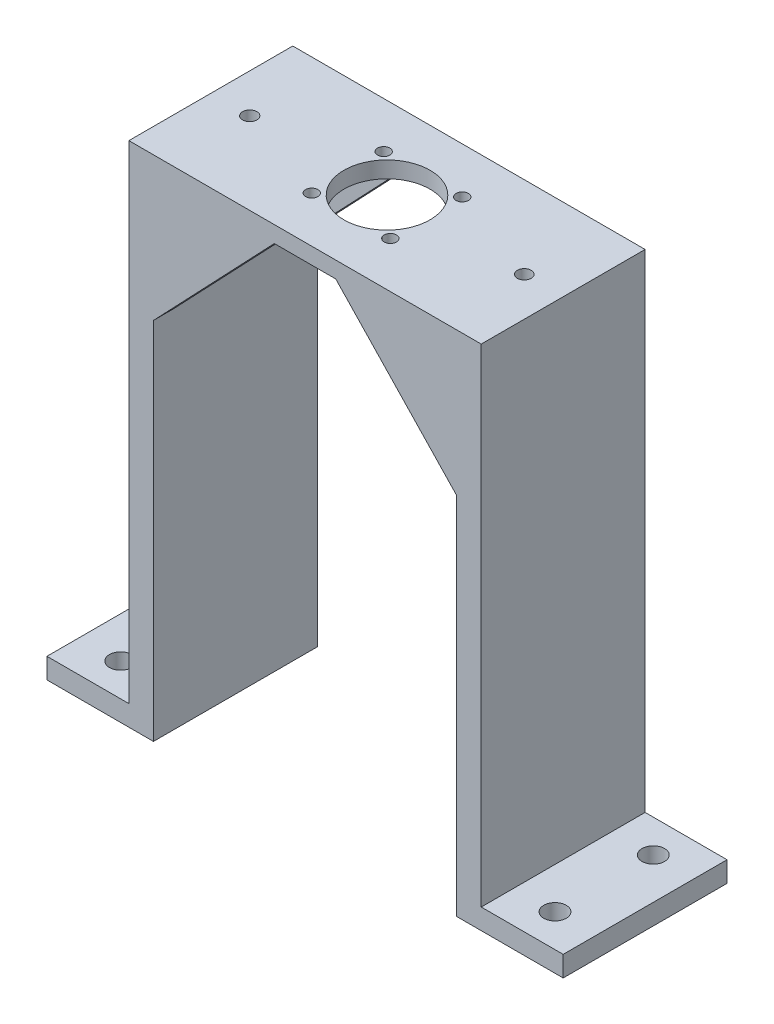
SolidWorks part; units mm, degrees
ref_plane "Plan de face" through (0, 0, 0) normal (0, 0, 1) x (1, 0, 0)
ref_plane "Plan de dessus" through (0, 0, 0) normal (0, 1, 0) x (1, 0, 0)
ref_plane "Plan de droite" through (0, 0, 0) normal (1, 0, 0) x (0, 0, -1)
sketch "Esquisse1" plane through (0, 0, 0) normal (0, 1, 0) x (1, 0, 0)
  line L1 (0, 0) -> (86, 0)
  line L2 (0, 0) -> (0, 40)
  line L3 (0, 40) -> (86, 40)
  line L4 (86, 0) -> (86, 40)
  dimension "D1" = 40
  dimension "D2" = 86
extrude "Boss.-Extru.1" add sketch "Esquisse1" along normal blind 4
sketch "Esquisse2" plane through (0, 4, 0) normal (0, 1, 0) x (1, 0, 0)
  line L0 (0, 0) -> (86, 40) construction
  line L1 (86, 40) -> (0, 40) construction
  line L2 (0, 40) -> (86, 0) construction
  line L3 (0, 0) -> (86, 0) construction
  line L4 (86, 0) -> (86, 40) construction
  circle A0 centre (43, 20) radius 10.5
  point P8 (43, 20)
  dimension "D1" = 21
  dimension "D2" = 0
extrude "Enlèv. mat.-Extru.1" cut sketch "Esquisse2" against normal through all
sketch "Esquisse3" plane through (0, 0, 0) normal (0, -1, 0) x (-1, 0, 0)
  line L0 (0, 0) -> (-86, 0) construction
  line L1 (0, 40) -> (-6, 40)
  line L2 (0, 40) -> (0, 0)
  line L3 (0, 0) -> (-6, 0)
  line L4 (-6, 40) -> (-6, 0)
  line L5 (-86, 40) -> (0, 40) construction
  line L6 (-86, 0) -> (-80, 0)
  line L7 (-86, 0) -> (-86, 40)
  line L8 (-86, 40) -> (-80, 40)
  line L9 (-80, 0) -> (-80, 40)
  dimension "D1" = 6
  dimension "D2" = 6
extrude "Boss.-Extru.2" add sketch "Esquisse3" along normal blind 120
sketch "Esquisse4" plane through (0, 0, 0) normal (-1, 0, 0) x (0, 0, 1)
  line L0 (0, 4) -> (0, -120) construction
  line L1 (-40, -120) -> (0, -120)
  line L2 (-40, -120) -> (-40, -115)
  line L3 (-40, -115) -> (0, -115)
  line L4 (0, -120) -> (0, -115)
  dimension "D1" = 5
extrude "Boss.-Extru.3" add sketch "Esquisse4" along normal blind 20
sketch "Esquisse5" plane through (86, 0, 0) normal (1, 0, 0) x (0, 0, -1)
  line L0 (40, 4) -> (40, -120) construction
  line L1 (0, -120) -> (40, -120)
  line L2 (0, -120) -> (0, -115)
  line L3 (0, -115) -> (40, -115)
  line L4 (40, -120) -> (40, -115)
  dimension "D1" = 5
extrude "Boss.-Extru.4" add sketch "Esquisse5" along normal blind 20
sketch "Esquisse6" plane through (0, -115, 0) normal (0, 1, 0) x (1, 0, 0)
  line L0 (-20, 40) -> (0, 0) construction
  line L1 (0, 0) -> (0, 40) construction
  line L2 (0, 40) -> (-20, 0) construction
  line L3 (-20, 0) -> (-20, 40) construction
  line L4 (-20, 0) -> (0, 0) construction
sketch "Esquisse7" plane through (0, -115, 0) normal (0, 1, 0) x (1, 0, 0)
  line L0 (106, 40) -> (86, 0) construction
  line L1 (86, 0) -> (106, 0) construction
  line L2 (106, 0) -> (86, 40) construction
sketch "Esquisse8" plane through (0, -115, 0) normal (0, 1, 0) x (1, 0, 0)
  line L0 (-20, 40) -> (0, 0) construction
  line L1 (0, 0) -> (-20, 0) construction
  line L2 (-20, 0) -> (0, 40) construction
  line L3 (-10, 20) -> (-10, 0) construction
  line L4 (-10, 0) -> (-10, 40) construction
  line L5 (-20, 40) -> (0, 40) construction
sketch "Esquisse9" plane through (0, -115, 0) normal (0, 1, 0) x (1, 0, 0)
  line L0 (106, 40) -> (86, 0) construction
  line L1 (86, 0) -> (106, 0) construction
  line L2 (106, 0) -> (86, 40) construction
  line L3 (86, 40) -> (86, 0) construction
  line L4 (106, 40) -> (86, 40) construction
  line L5 (96, 20) -> (96, 0) construction
  line L6 (96, 0) -> (96, 40) construction
hole_wizard "Dégagement M51" positions "Esquisse18" profile "Esquisse19" hole size "M5" standard "ISO" end condition up to next
sketch "Esquisse18" plane through (0, -115, 0) normal (0, 1, 0) x (1, 0, 0)
  line L0 (-10, 0) -> (-10, 40) construction
  line L1 (-10, 20) -> (-10, 0) construction
  line L2 (96, 0) -> (96, 40) construction
  line L3 (96, 20) -> (96, 0) construction
  point P0 (-10, 32)
  point P4 (-10, 8)
  point P8 (96, 32)
  point P12 (96, 8)
  dimension "D1" = 12
  dimension "D2" = 12
  dimension "D3" = 12
  dimension "D4" = 12
sketch "Esquisse19" plane through (-10, -115, -32) normal (1, 0, 0) x (0, 0, 1)
  line L0 (0, 0) -> (0, 5)
  line L1 (0, 5) -> (2.75, 5)
  line L2 (2.75, 5) -> (2.75, 0)
  line L5 (2.75, 0) -> (0, 0)
  line L11 (0, -6.35) -> (0, 107.95) construction
  dimension "Diamètre du perçage jusqu'au prochain" = 5.5
  dimension "Profondeur du perçage jusqu'au prochain" = 5
sketch "Esquisse32" plane through (6, 0, 0) normal (1, 0, 0) x (0, 0, -1)
  line L0 (0, -120) -> (0, 0) construction
  line L1 (40, 0) -> (0, 0)
  line L2 (40, 0) -> (40, -31)
  line L3 (40, -31) -> (0, -31)
  line L4 (0, 0) -> (0, -31)
  dimension "D1" = 31
extrude "Boss.-Extru.5" add sketch "Esquisse32" along normal blind 29.5
sketch "Esquisse33" plane through (80, 0, 0) normal (-1, 0, 0) x (0, 0, 1)
  line L0 (0, -120) -> (0, 0) construction
  line L1 (-40, 0) -> (0, 0)
  line L2 (-40, 0) -> (-40, -31)
  line L3 (-40, -31) -> (0, -31)
  line L4 (0, 0) -> (0, -31)
  dimension "D1" = 31
extrude "Boss.-Extru.6" add sketch "Esquisse33" along normal blind 29.5
sketch "Esquisse34" plane through (0, 0, 0) normal (0, 0, 1) x (1, 0, 0)
  line L0 (6, -31) -> (35.5, 0)
  line L1 (35.5, 0) -> (35.5, -31)
  line L2 (35.5, -31) -> (6, -31)
  line L3 (50.5, 0) -> (80, -31)
  line L4 (80, -31) -> (50.5, -31)
  line L5 (50.5, -31) -> (50.5, 0)
sketch "Esquisse38" plane through (0, 4, 0) normal (0, 1, 0) x (1, 0, 0)
  line L1 (52.5898, 11.2231) -> (33.4102, 11.2231)
  line L2 (52.5898, 11.2231) -> (52.5898, 28.7769)
  line L3 (52.5898, 28.7769) -> (33.4102, 28.7769)
  line L4 (33.4102, 11.2231) -> (33.4102, 28.7769)
  line L5 (52.5898, 11.2231) -> (33.4102, 28.7769) construction
  line L6 (52.5898, 28.7769) -> (33.4102, 11.2231) construction
  point P0 (43, 20)
  dimension "D1" = 26
sketch "Esquisse39" plane through (0, 4, 0) normal (0, 1, 0) x (1, 0, 0)
  circle A0 centre (33.4102, 28.7769) radius 1.5
  circle A1 centre (33.4102, 11.2231) radius 1.5
  circle A2 centre (52.5898, 11.2231) radius 1.5
  circle A3 centre (52.5898, 28.7769) radius 1.5
  dimension "D1" = 3
  dimension "D2" = 3
  dimension "D3" = 3
  dimension "D4" = 3
extrude "Enlèv. mat.-Extru.4" cut sketch "Esquisse39" against normal through all
sketch "Esquisse42" plane through (0, 0, 0) normal (0, 0, 1) x (1, 0, 0)
  line L0 (50.5, 0) -> (80, -31)
  line L1 (80, -31) -> (50.5, -31)
  line L2 (50.5, -31) -> (50.5, 0)
sketch "Esquisse43" plane through (35.5, 0, 0) normal (1, 0, 0) x (0, 0, -1)
  line L0 (27.3485, 0) -> (12.6515, 0) construction
  line L1 (5, 0) -> (35, 0)
  line L2 (5, 0) -> (5, -31)
  line L3 (5, -31) -> (35, -31)
  line L4 (35, 0) -> (35, -31)
  line L5 (0, -31) -> (40, -31) construction
  line L6 (0, 0) -> (0, -31) construction
  line L7 (40, -31) -> (40, 0) construction
  dimension "D1" = 5
  dimension "D2" = 5
sketch "Esquisse44" plane through (50.5, 0, 0) normal (-1, 0, 0) x (0, 0, 1)
  line L0 (-40, -31) -> (0, -31) construction
  line L1 (-5, -31) -> (-35, -31)
  line L2 (-5, -31) -> (-5, 0)
  line L3 (-5, 0) -> (-35, 0)
  line L4 (-35, -31) -> (-35, 0)
  line L5 (-12.6515, 0) -> (-27.3485, 0) construction
  line L6 (0, -31) -> (0, 0) construction
  line L7 (-40, 0) -> (-40, -31) construction
  dimension "D1" = 5
  dimension "D2" = 5
extrude "Enlèv. mat.-Extru.12" cut sketch "Esquisse43" against normal blind 29.5
extrude "Enlèv. mat.-Extru.13" cut sketch "Esquisse44" against normal blind 29.5
extrude "Enlèv. mat.-Extru.14" cut sketch "Esquisse34" against normal through all contours L3 L4 L5 | L0 L1 L2
sketch "Esquisse45" plane through (0, 4, 0) normal (0, 1, 0) x (1, 0, 0)
  line L0 (43, 20) -> (0, 20) construction
  line L1 (0, 40) -> (0, 0) construction
  line L2 (43, 20) -> (86, 20) construction
  line L3 (86, 0) -> (86, 40) construction
sketch "Esquisse47" plane through (0, 4, 0) normal (0, 1, 0) x (1, 0, 0)
  line L0 (43, 20) -> (0, 20) construction
  line L1 (43, 20) -> (86, 20) construction
  circle A0 centre (9.5, 20) radius 1.75
  circle A1 centre (76.5, 20) radius 1.7
  dimension "D1" = 3.5
  dimension "D2" = 3.4
  dimension "D3" = 33.5
  dimension "D4" = 33.5
extrude "Enlèv. mat.-Extru.15" cut sketch "Esquisse47" against normal through all
